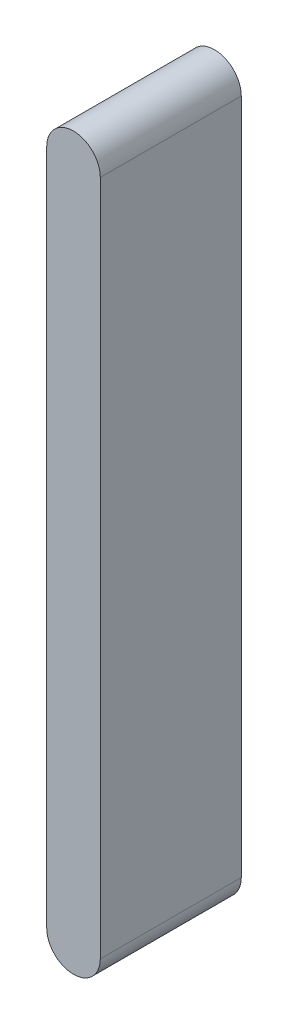
SolidWorks part; units mm, degrees
ref_plane "前视基准面" through (0, 0, 0) normal (0, 0, 1) x (1, 0, 0)
ref_plane "上视基准面" through (0, 0, 0) normal (0, 1, 0) x (1, 0, 0)
ref_plane "右视基准面" through (0, 0, 0) normal (1, 0, 0) x (0, 0, -1)
other "Configuration Table"
sketch "草图1" plane through (0, 0, 0) normal (0, 0, 1) x (1, 0, 0)
  line L0 (0, 17.3591) -> (0, -30.6409) construction
  line L1 (1.9, 17.3591) -> (1.9, -30.6409)
  line L2 (-1.9, 17.3591) -> (-1.9, -30.6409)
  arc A0 (1.9, 17.3591) -> (-1.9, 17.3591) centre (0, 17.3591) ccw
  arc A1 (-1.9, -30.6409) -> (1.9, -30.6409) centre (0, -30.6409) ccw
  point P3 (0, -6.6409)
  dimension "D1" = 1.9
  dimension "D2" = 48
extrude "凸台-拉伸1" add sketch "草图1" along normal blind 10 contours L1 A1 L2 A0
